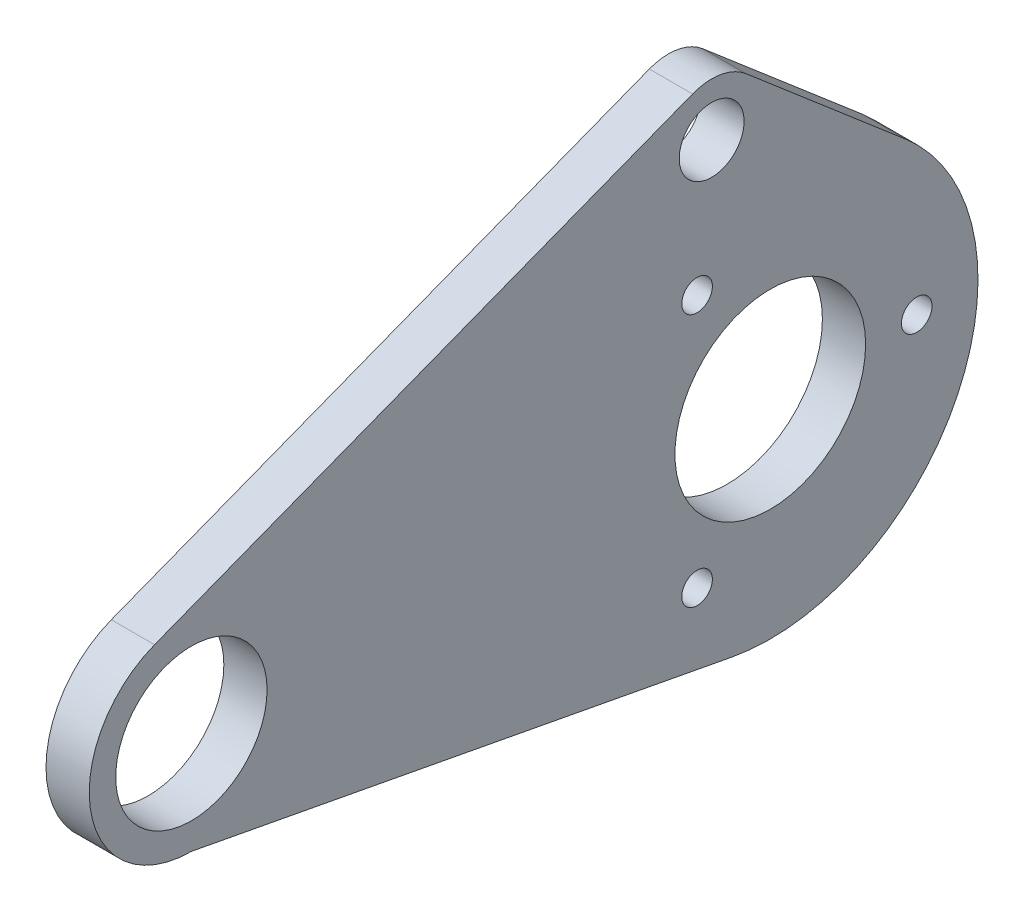
SolidWorks part; units mm, degrees
ref_plane "Front Plane" through (0, 0, 0) normal (0, 0, 1) x (1, 0, 0)
ref_plane "Top Plane" through (0, 0, 0) normal (0, 1, 0) x (1, 0, 0)
ref_plane "Right Plane" through (0, 0, 0) normal (1, 0, 0) x (0, 0, -1)
sketch "Sketch1" plane through (0, 0, 0) normal (1, 0, 0) x (0, 0, -1)
  line L4 (0, 15) -> (0, 11.1125) construction
  line L6 (0, 11.1125) -> (0, -11.1125) construction
  line L7 (0, -11.1125) -> (0, -15) construction
  line L8 (0, 15) -> (79.3449, 29.9712)
  line L9 (0, -15) -> (79.3449, -29.9712)
  line L10 (104.8218, 23.1808) -> (81.4329, 43.1804)
  line L11 (73.5899, 44.5213) -> (-5.4073, 13.9915)
  circle A0 centre (85, 0) radius 14
  circle A1 centre (0, 0) radius 11.1125
  arc A3 (79.3449, -29.9712) -> (79.3449, 29.9712) centre (85, 0) ccw
  arc A5 (0, 15) -> (0, -15) centre (0, 0) ccw
  arc A6 (79.3449, 29.9712) -> (79.3449, -29.9712) centre (85, 0) ccw construction
  arc A7 (0, -15) -> (0, 15) centre (0, 0) ccw construction
  circle A8 centre (0, 0) radius 85 construction
  circle A9 centre (0, 0) radius 75 construction
  circle A10 centre (76.3881, 37.2808) radius 4.7625
  circle A11 centre (76.3881, 37.2808) radius 7.7625
  dimension "D3" = 22.225
  dimension "D4" = 9.525
  dimension "D5" = 28
  dimension "D6" = 61
  dimension "D7" = 3
  dimension "D1" = 10
  dimension "D2" = 85
  dimension "D9" = 30
extrude "Boss-Extrude1" add sketch "Sketch1" along normal mid plane 6.35 contours A11 L8 A5 L9 A3 A0 A1 | A11 L11 A5 L8 | A11 L8 A10 | A11 L8 A3 L10 | L8 A11
hole_wizard "M4 Clearance Hole1" positions "Sketch2" profile "Sketch3" hole size "M4" standard "ANSI Metric" end condition through all
sketch "Sketch2" plane through (3.175, 0, 0) normal (1, 0, 0) x (0, 0, -1)
  line L0 (85, 0) -> (106.5, 0) construction
  line L1 (85, 0) -> (74.25, -18.6195) construction
  line L2 (85, 0) -> (74.25, 18.6195) construction
  point P2 (106.5, 0)
  point P12 (74.25, -18.6195)
  point P13 (74.25, 18.6195)
  dimension "D1" = 21.5
  dimension "D2" = 3
sketch "Sketch3" plane through (3.175, 18.6195, -74.25) normal (0, 1, 0) x (0, 0, -1)
  line L0 (0, 0) -> (0, 6.35)
  line L1 (0, 6.35) -> (2.25, 6.35)
  line L2 (2.25, 6.35) -> (2.25, 0)
  line L5 (2.25, 0) -> (0, 0)
  line L11 (0, -6.35) -> (0, 107.95) construction
  dimension "Thru Hole Dia." = 4.5
  dimension "Thru Hole Depth" = 6.35
hole_wizard "3/8 (0.3750) Dowel Hole1" positions "Sketch4" profile "Sketch5" hole size "3/8" standard "ANSI Inch"
sketch "Sketch4" plane through (3.175, 0, 0) normal (1, 0, 0) x (0, 0, -1)
  point P0 (65, 0)
  dimension "D1" = 65
sketch "Sketch5" plane through (3.175, 0, -65) normal (0, 1, 0) x (0, 0, -1)
  line L0 (0, 0) -> (0, 6.35)
  line L1 (0, 6.35) -> (4.7625, 6.35)
  line L2 (4.7625, 6.35) -> (4.7625, 0)
  line L5 (4.7625, 0) -> (0, 0)
  line L11 (0, -6.35) -> (0, 107.95) construction
  dimension "Thru Hole Dia." = 9.525
  dimension "Thru Hole Depth" = 6.35
